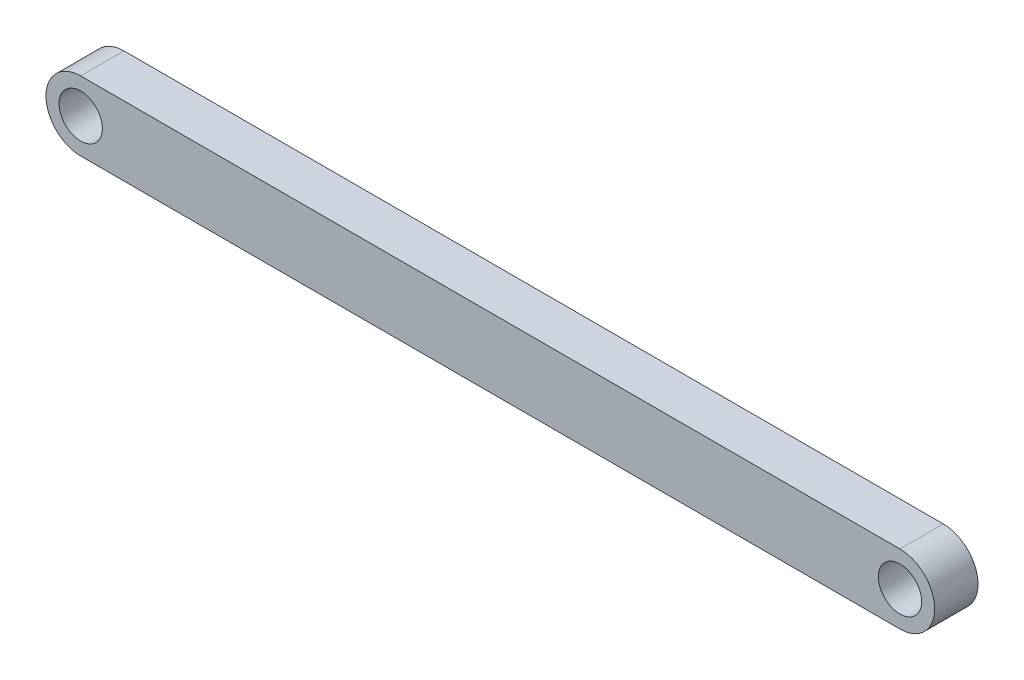
SolidWorks part; units mm, degrees
ref_plane "Front Plane" through (0, 0, 0) normal (0, 0, 1) x (1, 0, 0)
ref_plane "Top Plane" through (0, 0, 0) normal (0, 1, 0) x (1, 0, 0)
ref_plane "Right Plane" through (0, 0, 0) normal (1, 0, 0) x (0, 0, -1)
sketch "Sketch1" plane through (0, 0, 0) normal (0, 0, 1) x (1, 0, 0)
  line L0 (-94.5, 0) -> (94.5, 0) construction
  line L1 (-94.5, 8) -> (94.5, 8)
  line L2 (-94.5, -8) -> (94.5, -8)
  line L3 (0, -5.5) -> (0, 5.5) construction
  arc A0 (-94.5, 8) -> (-94.5, -8) centre (-94.5, 0) ccw
  arc A1 (94.5, -8) -> (94.5, 8) centre (94.5, 0) ccw
  circle A2 centre (-94.5, 0) radius 5
  circle A3 centre (94.5, 0) radius 5
  point P2 (0, 0)
  dimension "D2" = 10
  dimension "D3" = 3
  dimension "D1" = 189
extrude "Boss-Extrude1" add sketch "Sketch1" along normal mid plane 10
sketch "Sketch2" plane through (0, 0, -5) normal (0, 0, -1) x (-1, 0, 0)
  line L0 (-74.5, 0) -> (74.5, 0) construction
  line L1 (-74.5, 4) -> (74.5, 4)
  line L2 (-74.5, -4) -> (74.5, -4)
  line L3 (-94.5, 8) -> (94.5, 8) construction
  arc A0 (-74.5, 4) -> (-74.5, -4) centre (-74.5, 0) ccw
  arc A1 (74.5, -4) -> (74.5, 4) centre (74.5, 0) ccw
  circle A2 centre (-94.5, 0) radius 5 construction
  point P2 (0, 0)
  dimension "D1" = 4
  dimension "D2" = 20
extrude "Cut-Extrude1" cut sketch "Sketch2" against normal offset from surface (6 mm away) 4 up to face at (-89.5, 0, 5)
